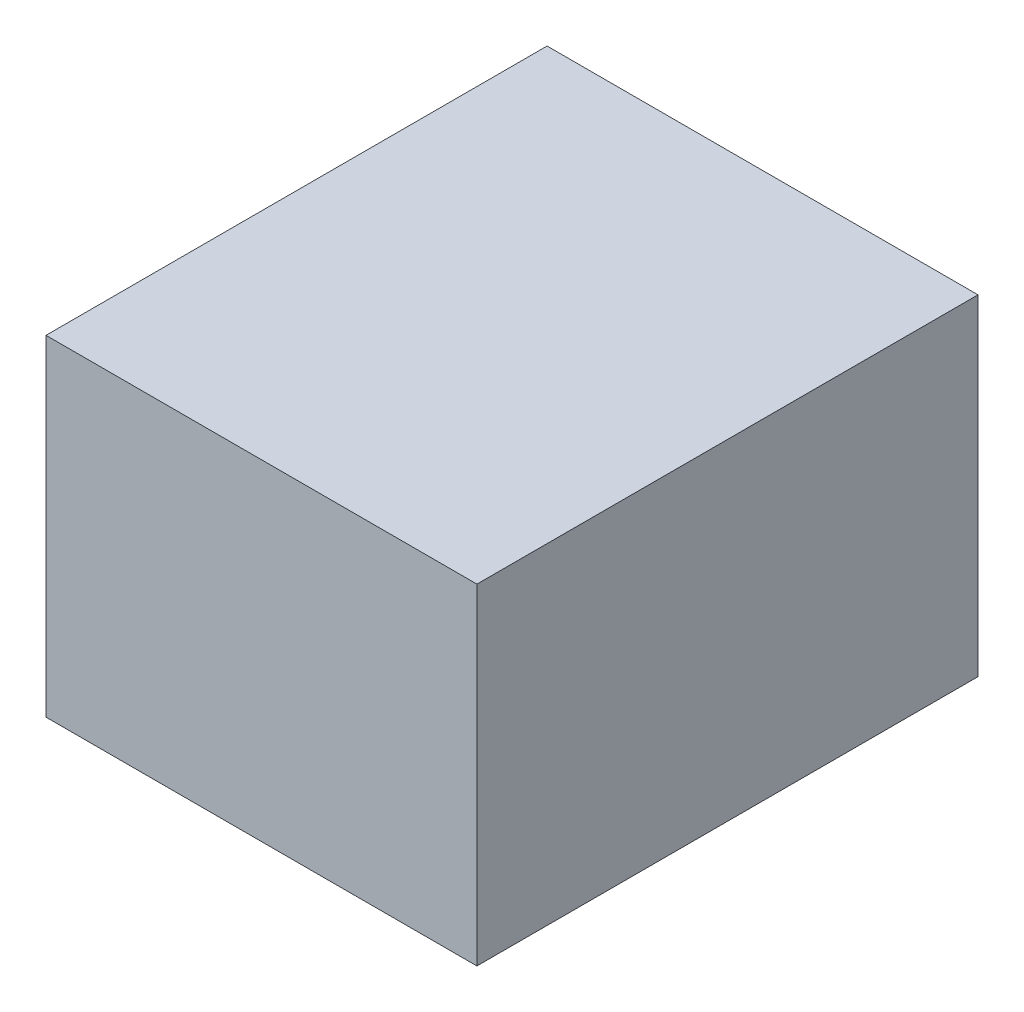
SolidWorks part; units mm, degrees
ref_plane "Front Plane" through (0, 0, 0) normal (0, 0, 1) x (1, 0, 0)
ref_plane "Top Plane" through (0, 0, 0) normal (0, 1, 0) x (1, 0, 0)
ref_plane "Right Plane" through (0, 0, 0) normal (1, 0, 0) x (0, 0, -1)
sketch "Sketch1" plane through (0, 0, 0) normal (0, 1, 0) x (1, 0, 0)
  line L1 (21.5, -25) -> (-21.5, -25)
  line L2 (21.5, -25) -> (21.5, 25)
  line L3 (21.5, 25) -> (-21.5, 25)
  line L4 (-21.5, -25) -> (-21.5, 25)
  line L5 (21.5, -25) -> (-21.5, 25) construction
  line L6 (21.5, 25) -> (-21.5, -25) construction
  point P0 (0, 0)
  dimension "D1" = 50
  dimension "D2" = 43
extrude "Boss-Extrude1" add sketch "Sketch1" along normal blind 33
